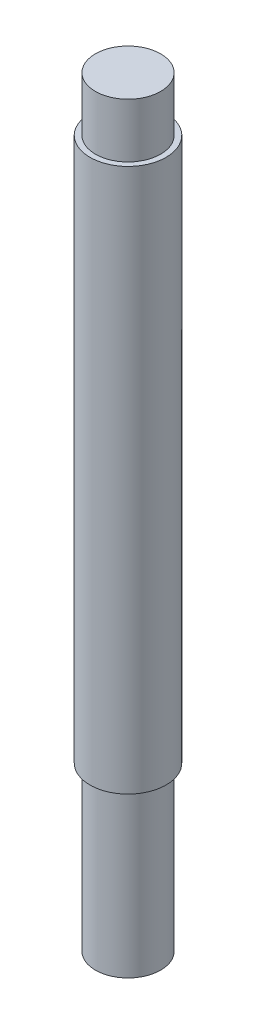
SolidWorks part; units mm, degrees
ref_plane "Alzado" through (0, 0, 0) normal (0, 0, 1) x (1, 0, 0)
ref_plane "Planta" through (0, 0, 0) normal (0, 1, 0) x (1, 0, 0)
ref_plane "Vista lateral" through (0, 0, 0) normal (1, 0, 0) x (0, 0, -1)
sketch "Croquis1" plane through (0, 0, 0) normal (0, 0, 1) x (1, 0, 0)
  line L0 (0, 0) -> (0, 30) construction
  line L1 (0, 30) -> (3, 30)
  line L2 (3, 30) -> (3, 25)
  line L3 (3, 25) -> (3.5, 25)
  line L4 (3.5, 25) -> (3.5, -25)
  line L5 (3.5, -25) -> (3, -25)
  line L6 (3, -25) -> (3, -40)
  line L7 (3, -40) -> (0, -40)
  line L8 (0, -40) -> (0, 30)
  dimension "D1" = 30
  dimension "D2" = 3
  dimension "D3" = 5
  dimension "D4" = 0.5
  dimension "D5" = 50
  dimension "D6" = 0.5
  dimension "D7" = 3
  dimension "D8" = 15
revolve "Revolución1" add sketch "Croquis1" angle 360 about L0
